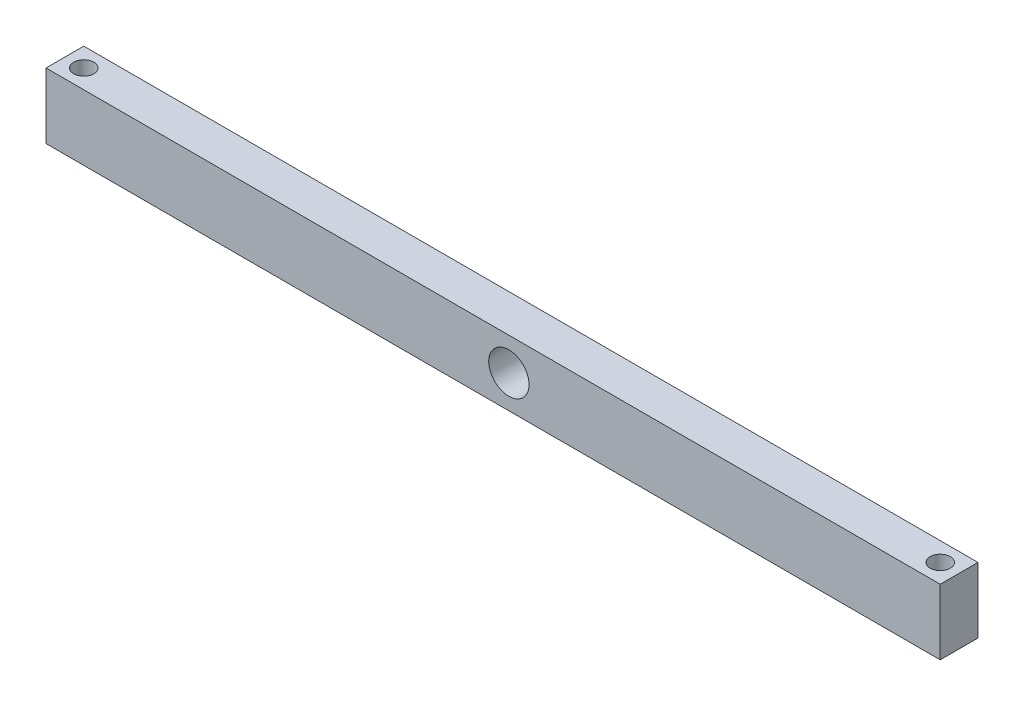
SolidWorks part; units mm, degrees
ref_plane "Front Plane" through (0, 0, 0) normal (0, 0, 1) x (1, 0, 0)
ref_plane "Top Plane" through (0, 0, 0) normal (0, 1, 0) x (1, 0, 0)
ref_plane "Right Plane" through (0, 0, 0) normal (1, 0, 0) x (0, 0, -1)
sketch "Sketch1" plane through (0, 0, 0) normal (0, 1, 0) x (1, 0, 0)
  line L1 (-54.9147, -19.5853) -> (16.0853, -19.5853)
  line L2 (-54.9147, -19.5853) -> (-54.9147, -16.5853)
  line L3 (-54.9147, -16.5853) -> (16.0853, -16.5853)
  line L4 (16.0853, -19.5853) -> (16.0853, -16.5853)
  dimension "D1" = 71
  dimension "D2" = 3
extrude "Boss-Extrude1" add sketch "Sketch1" along normal blind 5.2
sketch "Sketch2" plane through (0, 5.2, 0) normal (0, 1, 0) x (1, 0, 0)
  line L0 (16.0853, -19.5853) -> (16.0853, -16.5853) construction
  line L1 (16.0853, -16.5853) -> (-54.9147, -16.5853) construction
  line L2 (-54.9147, -16.5853) -> (-54.9147, -19.5853) construction
  circle A0 centre (-53.4147, -18.0853) radius 0.8
  circle A1 centre (14.5853, -18.0853) radius 0.8
  dimension "D1" = 1.6
  dimension "D2" = 1.5
  dimension "D3" = 1.5
  dimension "D4" = 1.6
  dimension "D5" = 1.5
  dimension "D6" = 1.5
extrude "Cut-Extrude1" cut sketch "Sketch2" against normal blind 5.2
sketch "Sketch3" plane through (0, 0, 16.5853) normal (0, 0, -1) x (-1, 0, 0)
  line L0 (-16.0853, 0) -> (54.9147, 0) construction
  line L1 (-16.0853, 5.2) -> (-16.0853, 0) construction
  circle A0 centre (18.1647, 2.6) radius 1.6
  dimension "D1" = 3.2
  dimension "D2" = 2.6
  dimension "D3" = 34.25
extrude "Cut-Extrude2" cut sketch "Sketch3" against normal blind 5.2
